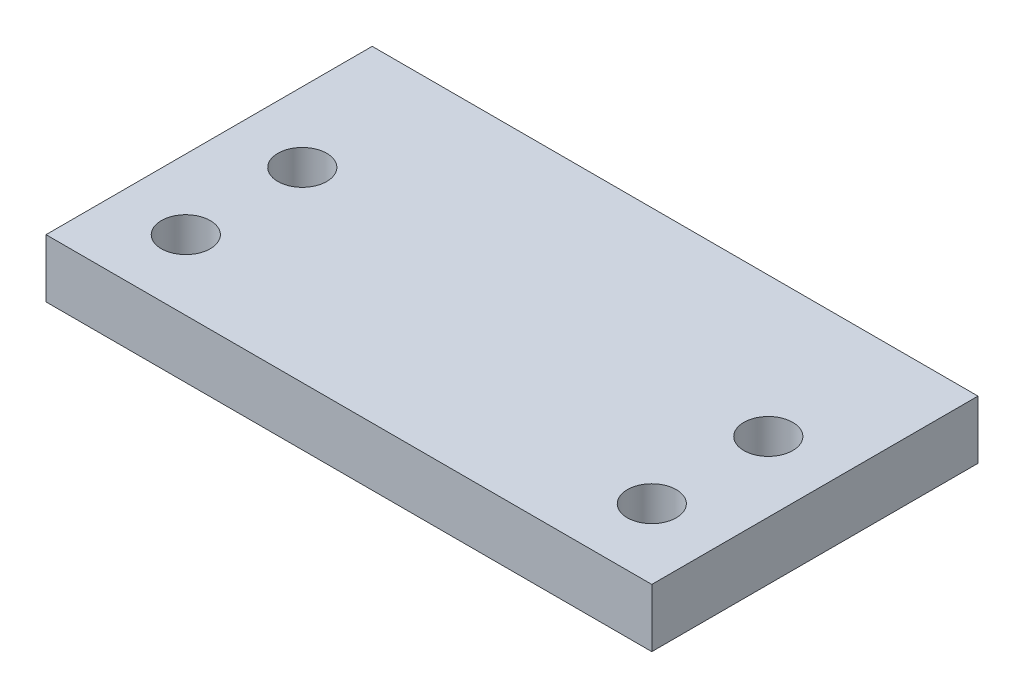
SolidWorks part; units mm, degrees
ref_plane "Front Plane" through (0, 0, 0) normal (0, 0, 1) x (1, 0, 0)
ref_plane "Top Plane" through (0, 0, 0) normal (0, 1, 0) x (1, 0, 0)
ref_plane "Right Plane" through (0, 0, 0) normal (1, 0, 0) x (0, 0, -1)
sketch "Sketch1" plane through (0, 0, 0) normal (0, 1, 0) x (1, 0, 0)
  line L0 (0, -3) -> (26, -3) construction
  line L1 (-26, -14) -> (26, -14)
  line L2 (-26, -14) -> (-26, 14)
  line L3 (-26, 14) -> (26, 14)
  line L4 (26, -14) -> (26, 14)
  line L5 (-26, -14) -> (26, 14) construction
  line L6 (-26, 14) -> (26, -14) construction
  line L7 (0, 14) -> (0, -14) construction
  circle A0 centre (20, -8) radius 2.1
  circle A1 centre (20, 2) radius 2.1
  circle A2 centre (-20, -8) radius 2.1
  circle A3 centre (-20, 2) radius 2.1
  point P0 (0, 0)
  dimension "D5" = 4.2
  dimension "D1" = 52
  dimension "D2" = 6
  dimension "D3" = 6
  dimension "D4" = 28
  dimension "D6" = 5
extrude "Boss-Extrude1" add sketch "Sketch1" along normal blind 5
equation "\"m4\"= 4.2"
equation "\"D5@Sketch1\"=\"m4\""
